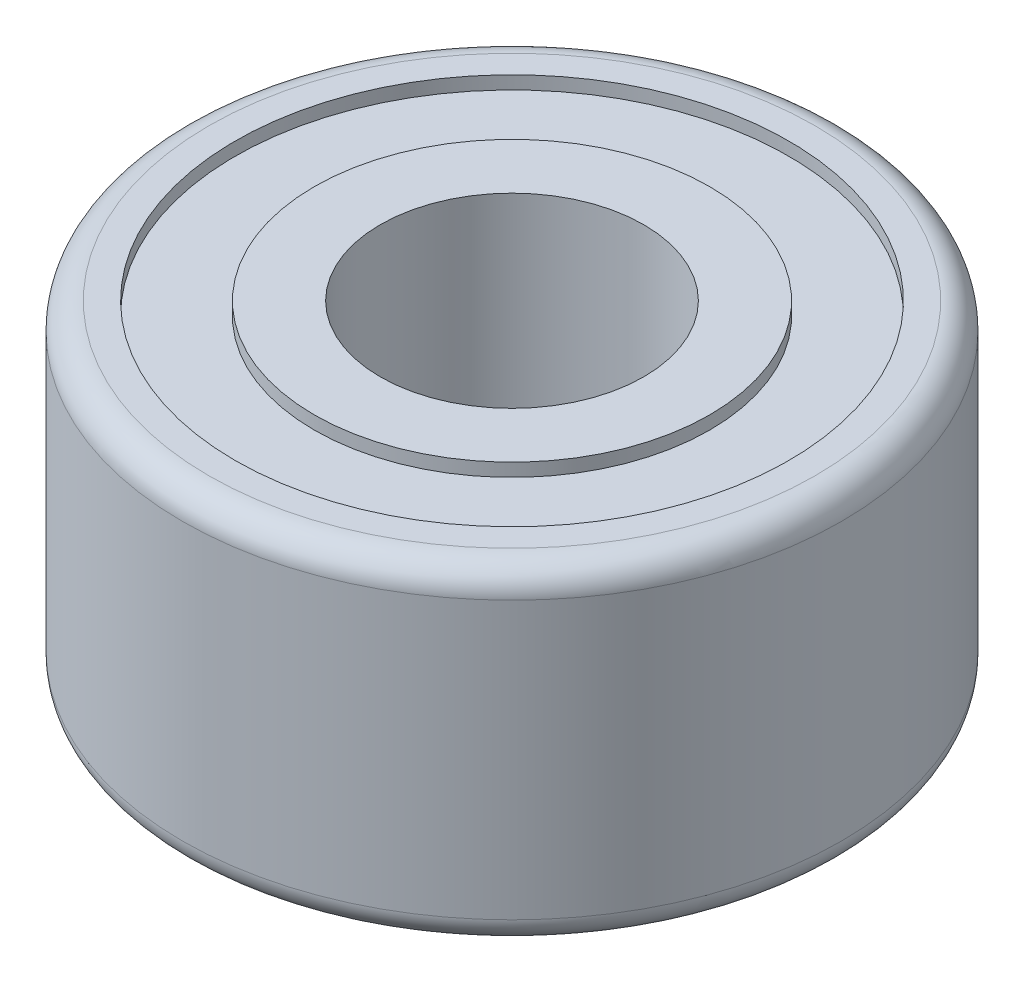
SolidWorks part; units mm, degrees
ref_plane "Front Plane" through (0, 0, 0) normal (0, 0, 1) x (1, 0, 0)
ref_plane "Top Plane" through (0, 0, 0) normal (0, 1, 0) x (1, 0, 0)
ref_plane "Right Plane" through (0, 0, 0) normal (1, 0, 0) x (0, 0, -1)
sketch "Sketch1" plane through (0, 0, 0) normal (0, 1, 0) x (1, 0, 0)
  circle A0 centre (0, 0) radius 1
  circle A1 centre (0, 0) radius 2.5
  dimension "D1" = 2
  dimension "D2" = 5
extrude "Boss-Extrude1" add sketch "Sketch1" along normal blind 2.5
fillet "Fillet1" radius 0.2 2 edges at (0, 0, 2.5) (0, 2.5, 2.5)
sketch "Sketch2" plane through (0, 2.5, 0) normal (0, 1, 0) x (1, 0, 0)
  circle A0 centre (0, 0) radius 1.5
  circle A1 centre (0, 0) radius 2.1
  dimension "D1" = 3
  dimension "D2" = 4.2
extrude "Cut-Extrude1" cut sketch "Sketch2" against normal blind 0.1
sketch "Sketch3" plane through (0, 0, 0) normal (0, -1, 0) x (1, 0, 0)
  circle A1 centre (0, 0) radius 2.1
  circle A2 centre (0, 0) radius 2.1
  circle A3 centre (0, 0) radius 1.5
  circle A4 centre (0, 0) radius 1.5
  dimension "D1" = 0
  dimension "D2" = 0
extrude "Cut-Extrude2" cut sketch "Sketch3" against normal blind 0.1
